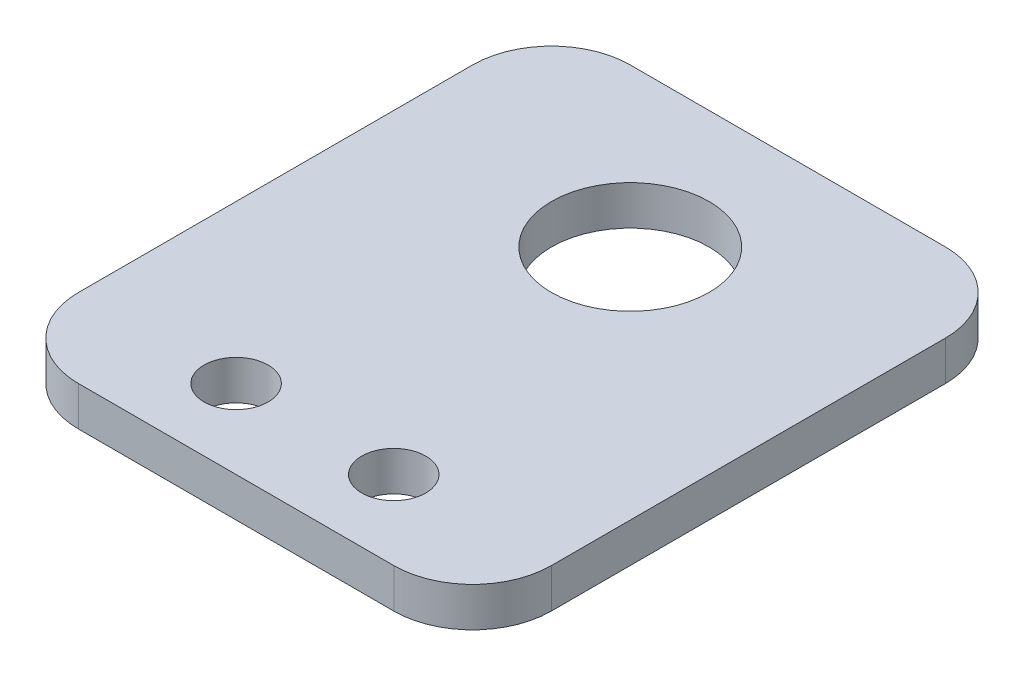
SolidWorks part; units mm, degrees
ref_plane "Front Plane" through (0, 0, 0) normal (0, 0, 1) x (1, 0, 0)
ref_plane "Top Plane" through (0, 0, 0) normal (0, 1, 0) x (1, 0, 0)
ref_plane "Right Plane" through (0, 0, 0) normal (1, 0, 0) x (0, 0, -1)
sketch "Sketch1" plane through (0, 0, 0) normal (0, 1, 0) x (1, 0, 0)
  line L1 (-25.4, 44.45) -> (25.4, 44.45)
  line L2 (-38.1, 31.75) -> (-38.1, -31.75)
  line L3 (-25.4, -44.45) -> (25.4, -44.45)
  line L4 (38.1, 31.75) -> (38.1, -31.75)
  line L5 (-38.1, 44.45) -> (38.1, -44.45) construction
  line L6 (-38.1, -44.45) -> (38.1, 44.45) construction
  arc A1 (25.4, -44.45) -> (38.1, -31.75) centre (25.4, -31.75) ccw
  arc A2 (-25.4, -44.45) -> (-38.1, -31.75) centre (-25.4, -31.75) cw
  arc A3 (38.1, 31.75) -> (25.4, 44.45) centre (25.4, 31.75) ccw
  arc A4 (-25.4, 44.45) -> (-38.1, 31.75) centre (-25.4, 31.75) ccw
  point P0 (0, 0)
  dimension "D5" = 12.7
  dimension "D1" = 76.2
  dimension "D2" = 88.9
extrude "Boss-Extrude1" add sketch "Sketch1" along normal blind 6.35
sketch "Sketch2" plane through (0, 6.35, 0) normal (0, 1, 0) x (1, 0, 0)
  line L0 (25.4, 44.45) -> (-25.4, 44.45) construction
  line L1 (0, 19.05) -> (0, 0) construction
  line L2 (-25.4, -44.45) -> (25.4, -44.45) construction
  circle A0 centre (0, 19.05) radius 12.7
  circle A1 centre (-12.7, -31.75) radius 5.1594
  circle A2 centre (12.7, -31.75) radius 5.1594
  dimension "D2" = 25.4
  dimension "D4" = 10.3187
  dimension "D1" = 25.4
  dimension "D3" = 25.4
  dimension "D5" = 12.7
extrude "Cut-Extrude1" cut sketch "Sketch2" against normal through all
